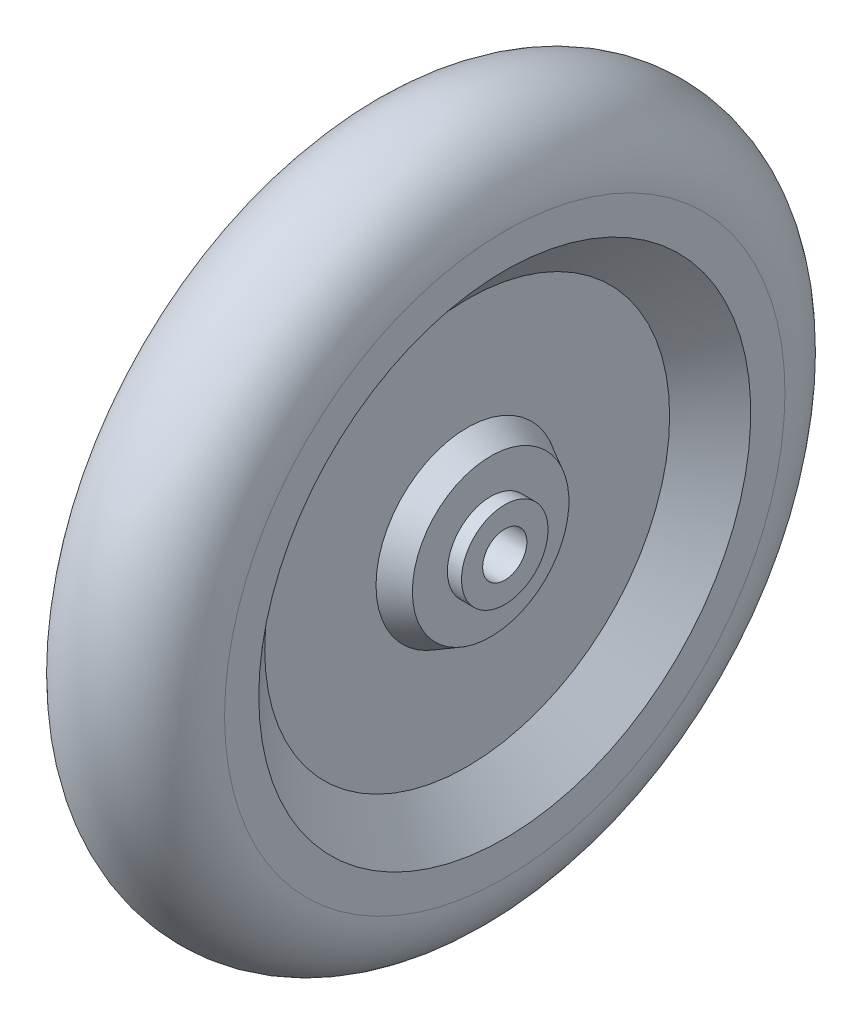
SolidWorks part; units mm, degrees
ref_plane "Front Plane" through (0, 0, 0) normal (0, 0, 1) x (1, 0, 0)
ref_plane "Top Plane" through (0, 0, 0) normal (0, 1, 0) x (1, 0, 0)
ref_plane "Right Plane" through (0, 0, 0) normal (1, 0, 0) x (0, 0, -1)
sketch "Sketch1" plane through (0, 0, 0) normal (0, 0, 1) x (1, 0, 0)
  line L0 (-15.875, 4.7625) -> (15.875, 4.7625)
  line L1 (7.7821, 43.5872) -> (7.7821, 19.6238)
  line L2 (15.875, 4.7625) -> (15.875, 9.311)
  line L3 (-1000, 0) -> (49000, 0) construction
  line L4 (0, -1000) -> (0, 49000) construction
  line L5 (15.875, 9.311) -> (12.8385, 9.311)
  line L6 (12.8385, 9.311) -> (12.8385, 16.8509)
  line L7 (12.8385, 16.8509) -> (7.7821, 19.6238)
  line L8 (7.7821, 43.5872) -> (15.875, 52.9601)
  line L9 (15.875, 52.9601) -> (15.875, 60.325)
  line L10 (-15.875, 4.7625) -> (-15.875, 9.311)
  line L11 (-15.875, 9.311) -> (-12.8385, 9.311)
  line L12 (-12.8385, 9.311) -> (-12.8385, 16.8509)
  line L13 (-12.8385, 16.8509) -> (-7.7821, 19.6238)
  line L14 (-7.7821, 43.5872) -> (-7.7821, 19.6238)
  line L15 (-7.7821, 43.5872) -> (-15.875, 52.9601)
  line L16 (-15.875, 52.9601) -> (-15.875, 60.325)
  arc A0 (15.875, 60.325) -> (-15.875, 60.325) centre (0, 60.325) ccw
  point P5 (0, 4.7625)
  dimension "D3" = 55.5625
  dimension "D1" = 4.7625
  dimension "D2" = 31.75
revolve "Revolve1" add sketch "Sketch1" angle 360 about L3
